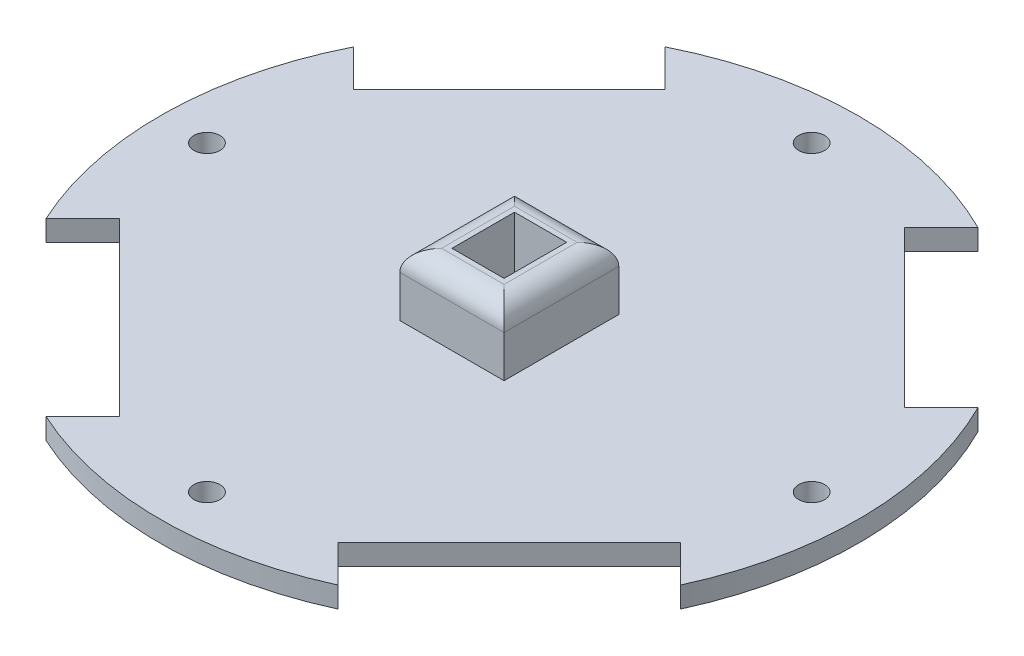
SolidWorks part; units mm, degrees
ref_plane "Front Plane" through (0, 0, 0) normal (0, 0, 1) x (1, 0, 0)
ref_plane "Top Plane" through (0, 0, 0) normal (0, 1, 0) x (1, 0, 0)
ref_plane "Right Plane" through (0, 0, 0) normal (1, 0, 0) x (0, 0, -1)
sketch "Sketch1" plane through (0, 0, 0) normal (0, 1, 0) x (1, 0, 0)
  circle A0 centre (0, 0) radius 67
  circle A1 centre (0, 58) radius 2.5
  circle A2 centre (58, 0) radius 2.5
  circle A3 centre (0, -58) radius 2.5
  circle A4 centre (-58, 0) radius 2.5
  point P10 (-21.3456, -19.7323)
  dimension "D1" = 58
extrude "Boss-Extrude1" add sketch "Sketch1" along normal blind 4 contours A0 A4 A3 A2 A1
sketch "Sketch2" plane through (0, 4, 0) normal (0, 1, 0) x (1, 0, 0)
  circle A1 centre (0, 0) radius 2
  point P0 (0, 0)
  dimension "D1" = 4
extrude "Cut-Extrude1" cut sketch "Sketch2" against normal blind 4
sketch "Sketch4" plane through (0, 4, 0) normal (0, 1, 0) x (1, 0, 0)
  line L1 (-5, 6) -> (5, 6)
  line L2 (-5, 6) -> (-5, -6)
  line L3 (-5, -6) -> (5, -6)
  line L4 (5, 6) -> (5, -6)
  line L5 (-5, 6) -> (5, -6) construction
  line L6 (-5, -6) -> (5, 6) construction
  line L7 (-10, 11) -> (10, 11)
  line L8 (-10, 11) -> (-10, -11)
  line L9 (-10, -11) -> (10, -11)
  line L10 (10, 11) -> (10, -11)
  line L11 (-10, 11) -> (10, -11) construction
  line L12 (-10, -11) -> (10, 11) construction
  point P0 (0, 0)
  point P6 (0, 0)
  dimension "D1" = 10
  dimension "D2" = 12
  dimension "D3" = 22
  dimension "D4" = 20
extrude "Boss-Extrude2" add sketch "Sketch4" along normal blind 12 contours L7 L10 L9 L8
fillet "Fillet1" radius 4 4 edges at (0, 16, 11) (10, 16, 0) (0, 16, -11) (-10, 16, 0)
fillet "Fillet2" radius 3 1 edges at (0, 0, 2)
sketch "Sketch5" plane through (0, 4, 0) normal (0, 1, 0) x (1, 0, 0)
  line L4 (59.9083, 30) -> (52.8372, 22.9289)
  line L8 (30, 59.9083) -> (22.9289, 52.8372)
  line L15 (52.8372, 22.9289) -> (22.9289, 52.8372)
  line L16 (-59.9083, 30) -> (-52.8372, 22.9289)
  line L17 (-30, 59.9083) -> (-22.9289, 52.8372)
  line L18 (-52.8372, 22.9289) -> (-22.9289, 52.8372)
  line L19 (-53.7976, -20.9289) -> (-20.9289, -53.7976)
  line L20 (-28, -60.8687) -> (-20.9289, -53.7976)
  line L21 (-60.8687, -28) -> (-53.7976, -20.9289)
  line L22 (53.7976, -20.9289) -> (20.9289, -53.7976)
  line L23 (28, -60.8687) -> (20.9289, -53.7976)
  line L24 (60.8687, -28) -> (53.7976, -20.9289)
  arc A9 (-60.8687, -28) -> (-28, -60.8687) centre (0, 0) ccw
  arc A10 (-30, 59.9083) -> (-59.9083, 30) centre (0, 0) ccw
  arc A11 (59.9083, 30) -> (30, 59.9083) centre (0, 0) ccw
  arc A12 (28, -60.8687) -> (60.8687, -28) centre (0, 0) ccw
  dimension "D1" = 10
  dimension "D2" = 10
  dimension "D3" = 10
  dimension "D4" = 10
extrude "Cut-Extrude2" cut sketch "Sketch5" against normal blind 10
sketch "Sketch7" plane through (0, 4, 0) normal (0, 1, 0) x (1, 0, 0)
  circle A0 centre (0, 4.5) radius 0.75
  circle A1 centre (0, -4.5) radius 0.75
  dimension "D1" = 4.5
  dimension "D2" = 4.5
extrude "Cut-Extrude3" cut sketch "Sketch7" against normal blind 10
sketch "Sketch8" plane through (0, 4, 0) normal (0, 1, 0) x (1, 0, 0)
  line L1 (-5, -6) -> (5, -6)
  line L2 (-5, -6) -> (-5, 6)
  line L3 (-5, 6) -> (5, 6)
  line L4 (5, -6) -> (5, 6)
  line L5 (-5, -6) -> (5, 6) construction
  line L6 (-5, 6) -> (5, -6) construction
  point P0 (0, 0)
extrude "Cut-Extrude4" cut sketch "Sketch8" against normal blind 2
